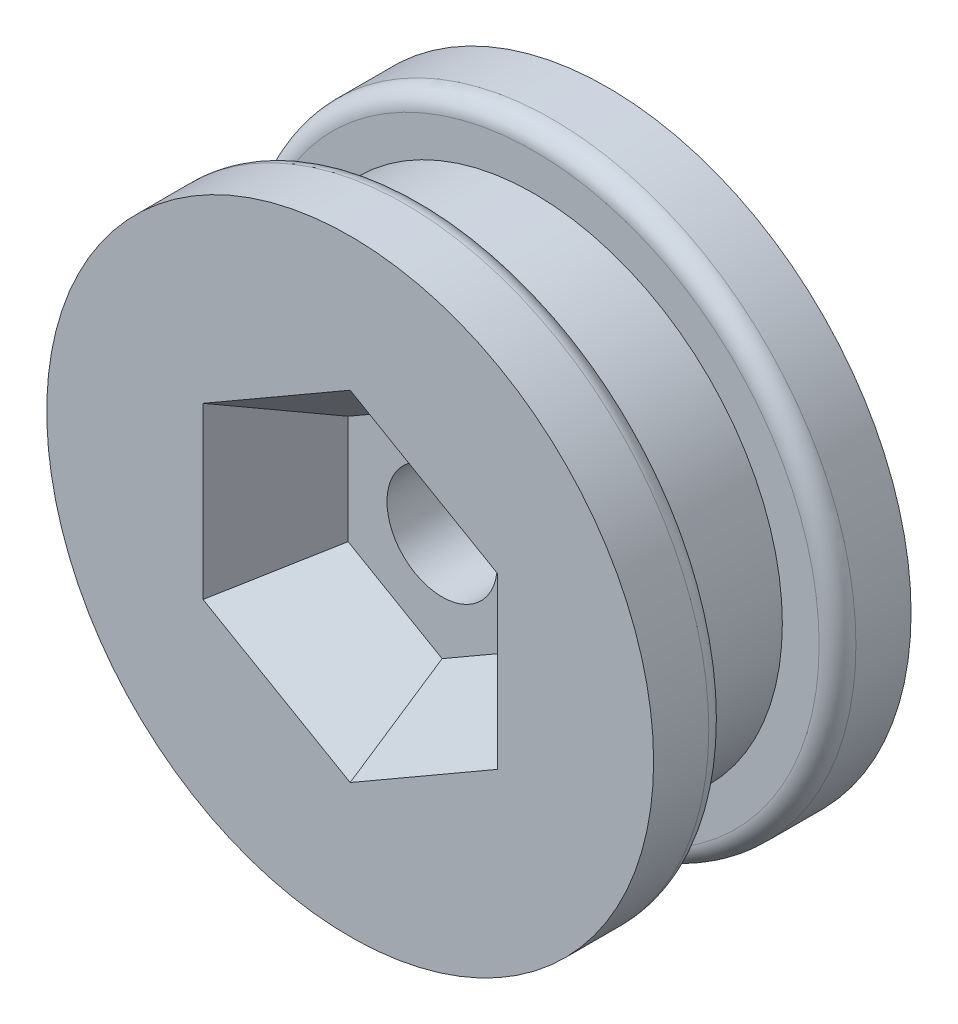
SolidWorks part; units mm, degrees
ref_plane "Front Plane" through (0, 0, 0) normal (0, 0, 1) x (1, 0, 0)
ref_plane "Top Plane" through (0, 0, 0) normal (0, 1, 0) x (1, 0, 0)
ref_plane "Right Plane" through (0, 0, 0) normal (1, 0, 0) x (0, 0, -1)
sketch "Sketch2" plane through (0, 0, 0) normal (1, 0, 0) x (0, 0, -1)
  line L0 (-7, 3) -> (-7, 16.5)
  line L1 (-7, 16.5) -> (-3, 16.5)
  line L2 (-3, 16.5) -> (-3, 13.5)
  line L3 (-3, 13.5) -> (3, 13.5)
  line L4 (0, -20.9183) -> (0, 20.9183) construction
  line L5 (-7, 3) -> (7, 3)
  line L6 (3, 16.5) -> (3, 13.5)
  line L7 (7, 16.5) -> (3, 16.5)
  line L8 (7, 3) -> (7, 16.5)
  line L9 (0, 0) -> (15.424, 0)
  point P10 (0, 0)
  point P13 (0, 3)
  point P14 (0, 13.5)
  dimension "D1" = 13.5
  dimension "D2" = 3
  dimension "D3" = 6
  dimension "D4" = 4
  dimension "D5" = 3
revolve "Revolve1" add sketch "Sketch2" angle 360 about L9
fillet "Fillet2" radius 1 2 edges at (16.5, 0, -3) (16.5, 0, 3)
sketch "Sketch5" plane through (0, 0, -7) normal (0, 0, -1) x (-1, 0, 0)
  line L1 (0, 9.2376) -> (-8, 4.6188)
  line L2 (-8, 4.6188) -> (-8, -4.6188)
  line L3 (-8, -4.6188) -> (0, -9.2376)
  line L4 (0, -9.2376) -> (8, -4.6188)
  line L5 (8, -4.6188) -> (8, 4.6188)
  line L6 (8, 4.6188) -> (0, 9.2376)
  circle A0 centre (0, 0) radius 8 construction
  dimension "D1" = 16
extrude "Cut-Extrude2" cut sketch "Sketch5" against normal blind 5 draft 30
mirror "Mirror1" about plane through (0, 0, 0) normal (0, 0, 1) of "Cut-Extrude2"
